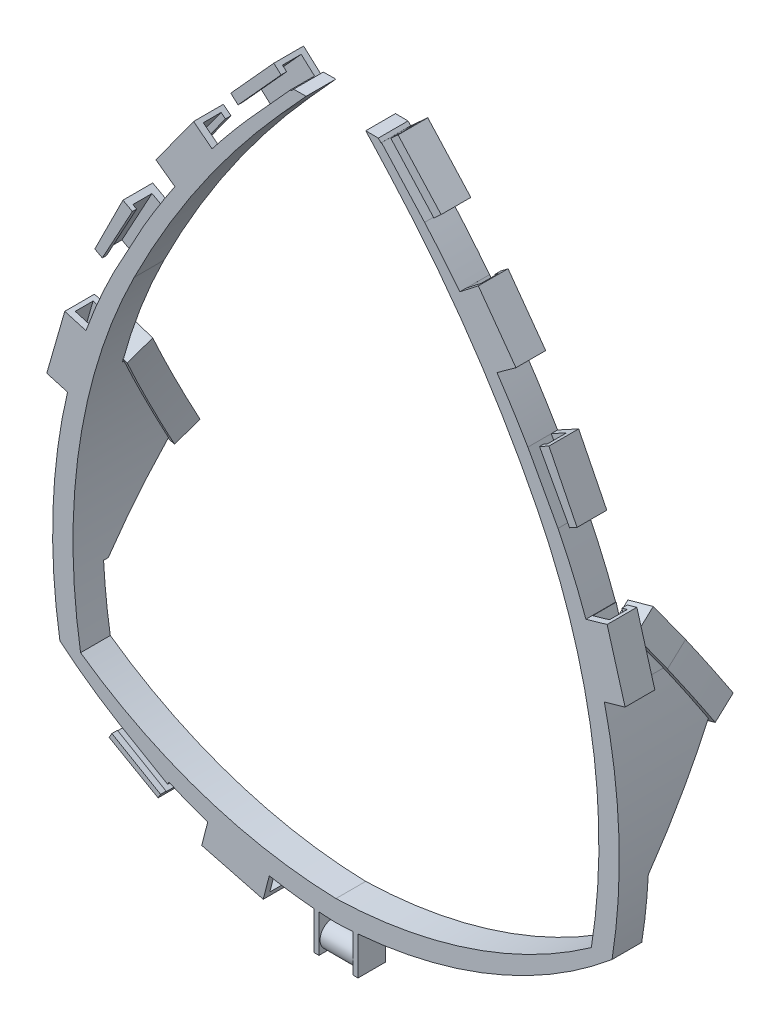
SolidWorks part; units mm, degrees
ref_plane "Front Plane" through (0, 0, 0) normal (0, 0, 1) x (1, 0, 0)
ref_plane "Top Plane" through (0, 0, 0) normal (0, 1, 0) x (1, 0, 0)
ref_plane "Right Plane" through (0, 0, 0) normal (1, 0, 0) x (0, 0, -1)
other "Graphic1"
other "Graphic (Closed) -1"
other "Graphic (Closed) -2"
other "Graphic (Closed) -3"
other "Graphic (Closed) -4"
other "Graphic (Closed) -5"
other "Graphic (Closed) -6"
other "Graphic (Closed) -7"
other "Graphic (Closed) -8"
other "Graphic (Closed) -9"
other "Graphic (Closed) -10"
other "Graphic (Closed) -11"
other "Graphic (Closed) -12"
other "Graphic (Closed) -13"
other "Graphic (Closed) -14"
other "Graphic (Closed) -15"
other "Graphic (Closed) -16"
other "Graphic (Closed) -17"
other "Graphic (Closed) -18"
other "Graphic (Closed) -19"
other "Graphic (Closed) -20"
other "Graphic (Closed) -21"
other "Graphic (Closed) -22"
other "Graphic (Closed) -23"
other "Graphic (Closed) -24"
other "Graphic (Closed) -25"
other "Graphic (Closed) -26"
other "Graphic (Closed) -27"
other "Graphic (Closed) -28"
other "Graphic (Closed) -29"
sketch "Sketch1" plane through (0, 0, 0) normal (0, 0, 1) x (1, 0, 0)
  line L0 (0, -51.2587) -> (0, 156.3738) construction
  line L1 (-7.0216, 140) -> (-12.8267, 133.5739)
  line L2 (7.0216, 140) -> (12.8267, 133.5739)
  line L3 (-14.5964, 135.0855) -> (-9.9688, 139.9698)
  line L4 (-9.9688, 139.9698) -> (-7.0216, 140)
  line L6 (14.5964, 135.0855) -> (9.9688, 139.9698)
  line L8 (7.0216, 140) -> (9.9688, 139.9698)
  arc A0 (-12.8267, 133.5739) -> (-47.5101, 82.8285) centre (156.4685, -19.3609) ccw
  arc A1 (-47.5101, 82.8285) -> (-60.1263, 0) centre (74.0258, 21.9413) ccw
  arc A2 (-60.1263, 0) -> (0, -20.0666) centre (3.113, 89.3736) ccw
  arc A3 (60.1263, 0) -> (0, -20.0666) centre (-3.113, 89.3736) cw
  arc A4 (47.5101, 82.8285) -> (60.1263, 0) centre (-74.0258, 21.9413) cw
  arc A5 (12.8267, 133.5739) -> (47.5101, 82.8285) centre (-156.4685, -19.3609) cw
  arc A6 (-65, 0) -> (-50.8527, 84.2769) centre (66.5753, 21.2388) cw
  arc A7 (-50.8527, 84.2769) -> (-14.5964, 135.0855) centre (142.5124, -15.3658) cw
  arc A8 (65, 0) -> (50.8527, 84.2769) centre (-66.5753, 21.2388) ccw
  arc A9 (50.8527, 84.2769) -> (14.5964, 135.0855) centre (-142.5124, -15.3658) ccw
  arc A10 (-65, 0) -> (0, -24.995) centre (3.8177, 81.9472) ccw
  arc A11 (65, 0) -> (0, -24.995) centre (-3.8177, 81.9472) cw
extrude "Boss-Extrude1" add sketch "Sketch1" along normal blind 7
sketch "Sketch2" plane through (0, 0, 7) normal (0, 0, 1) x (1, 0, 0)
  line L0 (10.5987, 139.305) -> (20.7341, 128.1225)
  line L1 (14.5964, 135.0855) -> (9.9688, 139.9698) construction
  line L2 (20.7341, 128.1225) -> (24.7581, 131.7698)
  line L3 (24.7581, 131.7698) -> (14.6227, 142.9522)
  line L4 (14.6227, 142.9522) -> (10.5987, 139.305)
  line L5 (28.7676, 117.9185) -> (33.5214, 121.6177)
  line L6 (33.5214, 121.6177) -> (42.3801, 109.3569)
  line L7 (42.3801, 109.3569) -> (37.2083, 105.6202)
  line L8 (37.2083, 105.6202) -> (28.7676, 117.9185)
  line L9 (45.1898, 94.5734) -> (52.2748, 81.5529)
  line L10 (52.2748, 81.5529) -> (56.767, 83.9973)
  line L11 (56.767, 83.9973) -> (50.141, 97.2676)
  line L12 (50.141, 97.2676) -> (45.1898, 94.5734)
  line L13 (58.083, 66.0889) -> (63.8479, 67.7441)
  line L14 (63.8479, 67.7441) -> (68.0782, 53.0113)
  line L15 (68.0782, 53.0113) -> (62.3132, 51.356)
  line L16 (62.3132, 51.356) -> (58.083, 66.0889)
  arc A0 (50.8527, 84.2769) -> (14.5964, 135.0855) centre (-142.5124, -15.3658) ccw construction
  arc A1 (65, 0) -> (50.8527, 84.2769) centre (-66.5753, 21.2388) ccw construction
extrude "Boss-Extrude2" add sketch "Sketch2" against normal up to surface (7 mm away) up to face at (0, 76.4404, 0)
sketch "Sketch4" plane through (-8.8767, 30.9153, 0) normal (0.276, -0.9612, 0) x (0.9612, 0.276, 0)
  line L0 (74.9855, 0) -> (74.9855, 7) construction
  line L1 (74.9855, 5.5) -> (79.0642, 5.5)
  line L2 (74.9855, 5.5) -> (74.9855, 1.3)
  line L3 (77.7311, 1.3) -> (79.0642, 1.3)
  line L4 (79.0642, 5.5) -> (79.0642, 1.3)
  line L5 (74.9855, 7) -> (80.0642, 7) construction
  line L6 (80.0642, 0) -> (80.0642, 7) construction
  line L7 (80.0642, 0) -> (74.9855, 0) construction
  line L10 (74.9855, 1.3) -> (74.9855, 0)
  line L11 (74.9855, 0) -> (77.7311, 0)
  line L12 (77.7311, 1.3) -> (77.7311, 0)
  dimension "D1" = 1.5
  dimension "D2" = 1
  dimension "D3" = 1.3
  dimension "D4" = 1.3331
extrude "Cut-Extrude1" cut sketch "Sketch4" against normal up to surface (15.3281 mm away) up to face at (61.3495, 67.0268, 3.5)
sketch "Sketch5" plane through (-22.2965, 40.9753, 0) normal (0.478, -0.8784, 0) x (0.8784, 0.478, 0)
  line L0 (84.8966, 0) -> (84.8966, 7) construction
  line L1 (88.0108, 6) -> (89.0108, 6)
  line L2 (84.8966, 6) -> (84.8966, 1.5)
  line L3 (84.8966, 1.5) -> (89.0108, 1.5)
  line L4 (89.0108, 6) -> (89.0108, 1.5)
  line L5 (84.8966, 7) -> (90.0108, 7) construction
  line L6 (90.0108, 0) -> (84.8966, 0) construction
  line L7 (90.0108, 0) -> (90.0108, 7) construction
  line L10 (84.8966, 6) -> (84.8966, 7)
  line L11 (84.8966, 7) -> (88.0108, 7)
  line L12 (88.0108, 6) -> (88.0108, 7)
  dimension "D1" = 1
  dimension "D2" = 1.5
  dimension "D3" = 1
  dimension "D4" = 2
extrude "Cut-Extrude2" cut sketch "Sketch5" against normal up to surface (14.8233 mm away) up to face at (47.6654, 95.9205, 3.5)
sketch "Sketch6" plane through (-37.3767, 51.7311, 0) normal (0.5856, -0.8106, 0) x (0.8106, 0.5856, 0)
  line L0 (92.8955, 0) -> (92.8955, 7) construction
  line L1 (92.8955, 5.5) -> (97.3965, 5.5)
  line L2 (92.8955, 5.5) -> (92.8955, 1.3)
  line L3 (96.0965, 1.3) -> (97.3965, 1.3)
  line L4 (97.3965, 5.5) -> (97.3965, 1.3)
  line L5 (92.8955, 7) -> (98.3965, 7) construction
  line L6 (98.3965, 0) -> (98.3965, 7) construction
  line L7 (98.3965, 0) -> (92.8955, 0) construction
  line L10 (92.8955, 1.3) -> (92.8955, 0)
  line L11 (92.8955, 0) -> (96.0965, 0)
  line L12 (96.0965, 1.3) -> (96.0965, 0)
  dimension "D1" = 1.5
  dimension "D2" = 1
  dimension "D3" = 1.3
  dimension "D4" = 1.3
extrude "Cut-Extrude3" cut sketch "Sketch6" against normal up to surface (15.0907 mm away)
sketch "Sketch7" plane through (-54.4018, 60.0219, 0) normal (0.6716, -0.7409, 0) x (0.7409, 0.6716, 0)
  line L0 (101.5906, 0) -> (101.5906, 7) construction
  line L1 (104.5365, 5.7) -> (105.8365, 5.7)
  line L2 (101.5906, 5.7) -> (101.5906, 1.3)
  line L3 (101.5906, 1.3) -> (105.8365, 1.3)
  line L4 (105.8365, 5.7) -> (105.8365, 1.3)
  line L5 (106.8365, 0) -> (101.5906, 0) construction
  line L6 (106.8365, 0) -> (106.8365, 7) construction
  line L8 (101.5906, 7) -> (106.8365, 7) construction
  line L11 (101.5906, 5.7) -> (101.5906, 7)
  line L12 (101.5906, 7) -> (104.5365, 7)
  line L13 (104.5365, 5.7) -> (104.5365, 7)
  dimension "D1" = 1.3
  dimension "D2" = 1
  dimension "D3" = 1.3
  dimension "D4" = 1.3
extrude "Cut-Extrude4" cut sketch "Sketch7" against normal up to surface (15.0922 mm away) up to face at (12.6107, 141.1286, 3.5)
mirror "Mirror2" about plane through (0, 0, 0) normal (1, 0, 0) of "Cut-Extrude4", "Cut-Extrude3", "Cut-Extrude1", "Cut-Extrude2", "Boss-Extrude2"
sketch "Sketch8" plane through (0, 0, 7) normal (0, 0, 1) x (1, 0, 0)
  line L0 (0, 0) -> (0, -34.8466) construction
  line L1 (-5.2, -22.8466) -> (-4, -22.8466)
  line L2 (-5.2, -22.8466) -> (-5.2, -33.6641)
  line L3 (-5.2, -33.6641) -> (-4, -33.6641)
  line L4 (-4, -22.8466) -> (-4, -33.6641)
  line L5 (0, -22.8466) -> (-10.4474, -22.8466) construction
  line L6 (4, -22.8466) -> (4, -33.6641)
  line L7 (5.2, -33.6641) -> (4, -33.6641)
  line L8 (5.2, -22.8466) -> (5.2, -33.6641)
  line L9 (5.2, -22.8466) -> (4, -22.8466)
  point P6 (0, 0)
  point P8 (0, 0)
  point P11 (-4, -22.8466)
  point P12 (0, 0)
  point P13 (0, 0)
  dimension "D4" = 34.8466
  dimension "D1" = 1.2
  dimension "D2" = 4
  dimension "D3" = 12
  dimension "D5" = 10.8175
extrude "Boss-Extrude3" add sketch "Sketch8" against normal offset from surface (6.5 mm away) 0.5 up to face at (0, 90.1411, 0)
sketch "Sketch9" plane through (4, 0, 0) normal (-1, 0, 0) x (0, 0, 1)
  line L0 (3.75, -33.6641) -> (3.75, -24.7174) construction
  line L1 (0.5, -33.6641) -> (7, -33.6641) construction
  circle A0 centre (3.75, -30.6641) radius 3
  point P6 (0, 0)
  dimension "D1" = 6
extrude "Boss-Extrude4" add sketch "Sketch9" along normal up to surface (8 mm away) up to face at (-4, -29.2207, 3.75)
sketch "Sketch11" plane through (0, 0, 0) normal (0, 0, -1) x (-1, 0, 0)
  line L0 (66.5352, 14.5491) -> (61.7076, 14.5491) construction
  line L1 (57.2553, 57.2042) -> (61.0815, 58.9761) construction
  line L2 (58.9664, 66.3425) -> (63.1967, 51.6097) construction
  line L3 (61.7076, 14.5491) -> (66.5352, 14.5491)
  line L4 (61.0815, 58.9761) -> (63.1967, 51.6097)
  line L5 (57.2553, 57.2042) -> (61.0815, 58.9761)
  line L6 (0, 0) -> (0, 92.1409) construction
  line L7 (-57.2553, 57.2042) -> (-61.0815, 58.9761) construction
  line L8 (-66.5352, 14.5491) -> (-61.7076, 14.5491) construction
  line L9 (-57.2553, 57.2042) -> (-61.0815, 58.9761)
  line L10 (-61.0815, 58.9761) -> (-63.1967, 51.6097)
  line L11 (-61.7076, 14.5491) -> (-66.5352, 14.5491)
  arc A0 (60.1263, 0) -> (47.5101, 82.8285) centre (-74.0258, 21.9413) ccw construction
  arc A1 (65, 0) -> (63.1967, 51.6097) centre (-66.5753, 21.2388) ccw construction
  arc A2 (61.7076, 14.5491) -> (57.2553, 57.2042) centre (-74.0258, 21.9413) ccw
  arc A3 (65, 0) -> (63.1967, 51.6097) centre (-66.5753, 21.2388) ccw
  arc A4 (-61.7076, 14.5491) -> (-57.2553, 57.2042) centre (74.0258, 21.9413) cw
  arc M13 (47.5101, 82.8285) -> (60.1263, 0) centre (-74.0258, 21.9413) cw
  arc M37 (65, 0) -> (63.1967, 51.6097) centre (-66.5753, 21.2388) ccw
  line M38 (63.1967, 51.6097) -> (58.9664, 66.3425)
extrude "Boss-Extrude5" add sketch "Sketch11" along normal blind 15.1 contours L5 L3 M13 M37 M38
sketch "Sketch12" plane through (-72.0733, 20.6943, 0) normal (-0.9612, 0.276, 0) x (0, 0, 1)
  line L0 (0, 39.8285) -> (-15.1, 13.8932)
  line L1 (-15.1, 13.8932) -> (0, -4.3781)
  line L2 (0, -4.3781) -> (0, 39.8285)
  line L3 (-15.1, 13.8932) -> (-15.1, 39.8285)
  line L4 (-15.1, 39.8285) -> (0, 39.8285)
  line L5 (-15.1, 13.8932) -> (-16.7839, -4.3781)
  line L6 (-16.7839, -4.3781) -> (0, -4.3781)
  line L7 (-15.1, 32.1645) -> (-15.1, -4.3781) construction
  point P3 (0, 0)
  point P8 (0, 0)
  point P9 (-1.4905, -6.4772)
  point P10 (0, -4.3781)
  point P11 (0, -11.1583)
  point P12 (-15.1, 13.8932)
  point P15 (0, -4.3781)
  point P16 (0, -5.2066)
  point P17 (0, -4.3781)
  point P18 (0, 0)
  point P19 (0, -11.1583)
  point P20 (0, 0)
  point P21 (0, -11.1583)
  point P22 (0, -11.1583)
  line M6 (0, 39.8285) -> (-15.1, 39.8285)
  line M7 (-15.1, 39.8285) -> (-15.1, 32.1645)
  line M8 (-15.1, 32.1645) -> (5.5, 32.1645)
extrude "Cut-Extrude7" cut sketch "Sketch12" against normal blind 15.1 contours L3 L0 M8 | L0 M6 M7 M8 | L5 L6 L1
sketch "Sketch13" plane through (2.7827, 9.6914, -17.3183) normal (0.1389, 0.4836, -0.8642) x (-0.9903, 0.0678, -0.1212)
  line L11 (67.6005, 43.0783) -> (65.1716, 52.867)
  line L12 (65.1716, 52.867) -> (59.4631, 50.3106)
  line L13 (64.0156, 19.3969) -> (70.6628, 21.0463)
  line L14 (67.6005, 43.0783) -> (65.1716, 52.867)
  line L15 (65.1716, 52.867) -> (59.4631, 50.3106)
  line L16 (64.0156, 19.3969) -> (70.6628, 21.0463)
  spline S0 degree 3 poles (-2593.9862, -1268.3355) (1751.3891, 22.8393) (125.75, 484.081) (-2807.8141, 763.5295) knots -40.922043 -40.922043 -40.922043 -40.922043 50.876818 50.876818 50.876818 50.876818 only from (70.6628, 21.0463) to (67.6005, 43.0783)
  spline S1 degree 3 poles (-2856.5316, 561.9221) (-847.7239, 538.8073) (16.4004, 347.12) (103.5629, -244.2461) (-509.6626, -619.8122) (-2627.673, -1216.9814) knots -29.794576 -29.794576 -29.794576 -29.794576 0.5 0.5 27.59512 27.59512 27.59512 27.59512 only from (59.4631, 50.3106) to (64.0156, 19.3969)
  spline S2 degree 3 poles (70.6628, 21.0463) (70.1019, 28.4542) (69.0792, 35.7979) (67.6005, 43.0783) knots 0 0 0 0 1 1 1 1
  spline S3 degree 3 poles (59.4631, 50.3106) (60.6697, 45.2243) (61.6519, 40.1049) (63.1707, 29.8005) (63.7072, 24.6155) (64.0156, 19.3969) knots 0 0 0 0 0.5 0.5 1 1 1 1
  dimension "D1" = 1
extrude "Boss-Extrude10" add sketch "Sketch13" along normal blind 6 separate body contours S2 L14 L15 S3 L16
sketch "Sketch15" plane through (0.813, 2.8315, 1.7152) normal (-0.2385, -0.8306, -0.5032) x (0.9711, -0.204, -0.1236)
  line L0 (-69.6005, -33.3341) -> (-62.8221, -32.3548) construction
  line L1 (-69.1716, -36.3032) -> (-70.0295, -30.3649) construction
  line L2 (-62.3931, -35.324) -> (-63.251, -29.3856) construction
  line L3 (-66.6403, -29.8753) -> (-65.7823, -35.8136) construction
  line L4 (-63.251, -29.3856) -> (-70.0295, -30.3649) construction
  line L5 (-62.3931, -35.324) -> (-69.1716, -36.3032) construction
  circle A0 centre (-66.2113, -32.8444) radius 2
  dimension "D1" = 4
extrude "Cut-Extrude10" cut sketch "Sketch15" against normal blind 6
sketch "Sketch23" plane through (0, 0, 0) normal (0, 0, -1) x (-1, 0, 0)
  line L0 (-58.9664, 66.3425) -> (-63.1967, 51.6097) construction
  line L1 (-61.0815, 58.9761) -> (-63.1967, 51.6097)
  line L2 (61.7076, 14.5491) -> (-61.7076, 14.5491) construction
  line L3 (-61.7076, 14.5491) -> (-66.5352, 14.5491)
  line L4 (-61.0815, 58.9761) -> (-57.0727, 57.8772)
  arc A0 (-47.5101, 82.8285) -> (-60.1263, 0) centre (74.0258, 21.9413) ccw construction
  arc A1 (-63.1967, 51.6097) -> (-65, 0) centre (66.5753, 21.2388) ccw construction
  arc A2 (-57.0727, 57.8772) -> (-61.7076, 14.5491) centre (74.0258, 21.9413) ccw
  arc A3 (-63.1967, 51.6097) -> (-66.5352, 14.5491) centre (66.5753, 21.2388) ccw
extrude "Boss-Extrude11" add sketch "Sketch23" along normal blind 15.1
sketch "Sketch25" plane through (72.0733, 20.6943, 0) normal (0.9612, 0.276, 0) x (0, 0, -1)
  line L12 (0, 43.3612) -> (15.1, 18.8488)
  line L14 (15.1, -4.3781) -> (15.1, 32.1645) construction
  line L15 (15.1, 18.8488) -> (0, -4.3781)
  line L16 (15.1, -4.3781) -> (0, -4.3781) construction
  line L17 (0, -4.3781) -> (0, 43.3612)
  line L18 (0, 43.3612) -> (15.1, 43.3612)
  line L19 (15.1, 43.3612) -> (15.1, 18.8488)
  line L20 (0, -4.3781) -> (15.1, -4.3781)
  line L21 (15.1, -4.3781) -> (15.1, 18.8488)
  line L22 (0, 47.4926) -> (0, 39.8285) construction
  point P2 (0, 41.1499)
  point P5 (15.1, 39.8285)
  point P12 (15.1, 39.8285)
  point P14 (0, 43.3612)
  line M7 (-5.5, 32.1645) -> (15.1, 32.1645)
  line M8 (15.1, 32.1645) -> (15.1, 39.8285)
  line M9 (15.1, 39.8285) -> (0, 39.8285)
extrude "Cut-Extrude17" cut sketch "Sketch25" against normal blind 15.1 contours L19 L18 L12 M9 | L12 M9 M7 M8 | L19 L12 M7 | L20 L21 L15
sketch "Sketch26" plane through (-3.2919, 11.4648, -19.3633) normal (-0.1447, 0.5041, -0.8514) x (-0.9895, -0.0737, 0.1246)
  line L6 (-70.7028, 24.6229) -> (-64.1456, 23.0199)
  line L7 (-59.8023, 49.4588) -> (-65.7958, 50.8343)
  line L8 (-65.7958, 50.8343) -> (-68.1726, 41.112)
  line L9 (-70.7028, 24.6229) -> (-64.1456, 23.0199)
  line L10 (-59.8023, 49.4588) -> (-65.7958, 50.8343)
  line L11 (-65.7958, 50.8343) -> (-68.1726, 41.112)
  spline S0 degree 3 poles (2553.4226, -1357.1942) (-1601.2379, 22.0884) (-280.8536, 501.934) (2833.0094, 687.1479) knots -34.995098 -34.995098 -34.995098 -34.995098 41.987823 41.987823 41.987823 41.987823 only from (-64.1456, 23.0199) to (-59.8023, 49.4588)
  spline S1 degree 3 poles (2813.5638, 726.7501) (-197.5299, 492.9563) (-1684.4402, 25.2795) (2563.2684, -1322.3636) knots -66.825246 -66.825246 -66.825246 -66.825246 56.862268 56.862268 56.862268 56.862268 only from (-68.1726, 41.112) to (-70.7028, 24.6229)
  spline S2 degree 3 poles (-64.1456, 23.0199) (-63.3366, 31.9378) (-61.8861, 40.7503) (-59.8023, 49.4588) knots 0 0 0 0 1 1 1 1
  spline S3 degree 3 poles (-68.1726, 41.112) (-69.2651, 35.6539) (-70.1092, 30.1576) (-70.7028, 24.6229) knots 0 0 0 0 1 1 1 1
  dimension "D1" = 1
extrude "Boss-Extrude12" add sketch "Sketch26" along normal blind 6
sketch "Sketch27" plane through (-1.675, 5.8336, 3.7388) normal (0.235, -0.8184, -0.5245) x (0.972, 0.1978, 0.1268)
  line L0 (66.9724, -33.0845) -> (66.0789, -39.0176) construction
  line L1 (70.3099, -33.5871) -> (63.6349, -32.5819) construction
  line L2 (69.4164, -39.5202) -> (62.7414, -38.515) construction
  line L3 (63.1881, -35.5484) -> (69.8632, -36.5536) construction
  line L4 (62.7414, -38.515) -> (63.6349, -32.5819) construction
  line L5 (69.4164, -39.5202) -> (70.3099, -33.5871) construction
  circle A0 centre (66.5256, -36.051) radius 2
  dimension "D1" = 4
extrude "Cut-Extrude18" cut sketch "Sketch27" against normal blind 6
sketch "Sketch28" plane through (0, 0, 7) normal (0, 0, 1) x (1, 0, 0)
  line L0 (-50.076, -8.2089) -> (-53.3977, -13.9048)
  line L1 (-53.3977, -13.9048) -> (-41.8731, -20.4722)
  line L2 (-41.8731, -20.4722) -> (-38.4013, -14.4166)
  line L3 (-38.4013, -14.4166) -> (-50.076, -8.2089)
  line L4 (-29.8998, -18.4582) -> (-31.6059, -25.0269)
  line L5 (-31.6059, -25.0269) -> (-17.1276, -28.7875)
  line L6 (-17.1276, -28.7875) -> (-15.4215, -22.2188)
  line L7 (-15.4215, -22.2188) -> (-29.8998, -18.4582)
extrude "Boss-Extrude13" add sketch "Sketch28" against normal up to surface (7 mm away) up to face at (0, -0.6714, 0)
sketch "Sketch29" plane through (-33.7953, 19.7085, 0) normal (-0.8638, 0.5038, 0) x (0, 0, 1)
  line L0 (0, -34.2919) -> (7, -34.2919) construction
  line L1 (1.3, -34.2919) -> (5.7, -34.2919)
  line L2 (1.3, -34.2919) -> (1.3, -37.9115)
  line L3 (1.3, -37.9115) -> (5.7, -37.9115)
  line L4 (5.7, -37.6115) -> (5.7, -37.9115)
  line L5 (0, -38.9115) -> (0, -34.2919) construction
  line L6 (0, -38.9115) -> (7, -38.9115) construction
  line L7 (7, -34.2919) -> (7, -38.9115) construction
  line L9 (5.7, -34.2919) -> (7, -34.2919)
  line L11 (5.7, -37.6115) -> (7, -37.6115)
  line L12 (7, -34.2919) -> (7, -37.6115)
  point P6 (1.3, -36.1017)
  dimension "D1" = 1.3
  dimension "D2" = 1
  dimension "D3" = 1.3
  dimension "D4" = 1.3
extrude "Cut-Extrude20" cut sketch "Sketch29" against normal up to surface (13.2307 mm away)
sketch "Sketch30" plane through (-23.5188, 6.1088, 0) normal (-0.9679, 0.2514, 0) x (0, 0, 1)
  line L0 (0, -32.1688) -> (7, -32.1688) construction
  line L1 (5.7, -26.4796) -> (1.3, -26.4796)
  line L2 (5.7, -26.4796) -> (5.7, -31.1688)
  line L3 (5.7, -31.1688) -> (1.3, -31.1688)
  line L4 (1.3, -29.8688) -> (1.3, -31.1688)
  line L5 (0, -32.1688) -> (0, -26.4796) construction
  line L6 (7, -26.4796) -> (7, -32.1688) construction
  line L8 (1.3, -26.4796) -> (0, -26.4796)
  line L10 (1.3, -29.8688) -> (0, -29.8688)
  line L11 (0, -26.4796) -> (0, -29.8688)
  dimension "D1" = 1
  dimension "D2" = 1.3
  dimension "D3" = 1.3
  dimension "D4" = 1.3
extrude "Cut-Extrude21" cut sketch "Sketch30" against normal up to surface (14.9588 mm away) up to face at (-16.411, -26.0284, 3.5)
